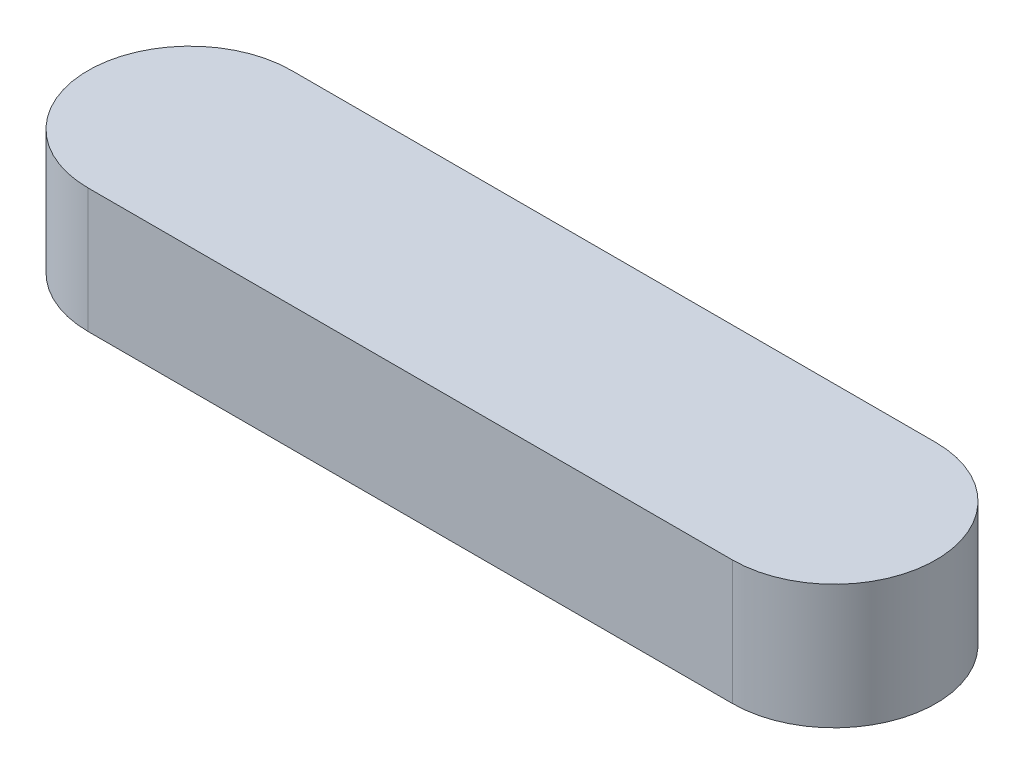
SolidWorks part; units mm, degrees
ref_plane "正面" through (0, 0, 0) normal (0, 0, 1) x (1, 0, 0)
ref_plane "平面" through (0, 0, 0) normal (0, 1, 0) x (1, 0, 0)
ref_plane "右側面" through (0, 0, 0) normal (1, 0, 0) x (0, 0, -1)
sketch "ｽｹｯﾁ1" plane through (0, 0, 0) normal (0, 1, 0) x (1, 0, 0)
  line L0 (0, 0) -> (57, 0) construction
  line L1 (0, 9) -> (57, 9)
  line L2 (0, -9) -> (57, -9)
  arc A0 (0, 9) -> (0, -9) centre (0, 0) ccw
  arc A1 (57, -9) -> (57, 9) centre (57, 0) ccw
  point P3 (28.5, 0)
  point P8 (0, 0)
extrude "ﾎﾞｽ - 押し出し1" add sketch "ｽｹｯﾁ1" along normal blind 11
